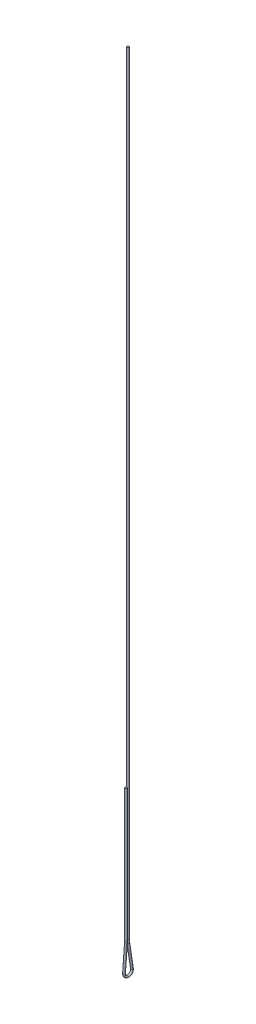
SolidWorks part; units mm, degrees
ref_plane "Front Plane" through (0, 0, 0) normal (0, 0, 1) x (1, 0, 0)
ref_plane "Top Plane" through (0, 0, 0) normal (0, 1, 0) x (1, 0, 0)
ref_plane "Right Plane" through (0, 0, 0) normal (1, 0, 0) x (0, 0, -1)
sketch "Sketch1" plane through (0, 0, 0) normal (1, 0, 0) x (0, 0, -1)
  line L1 (0, 21.5085) -> (0, 600)
  line L2 (0, 55) -> (0, -55) construction
  line L3 (55, 0) -> (-55, 0) construction
  line L4 (0.2263, 18.5085) -> (2.9661, 0.45)
  line L5 (-1.5, 20.7532) -> (-1.5, 120)
  line L6 (-1.5566, 19.2489) -> (-2.9915, 0.2256)
  circle A0 centre (0, 0) radius 2 construction
  arc A1 (-2.9915, 0.2256) -> (2.9661, 0.45) centre (0, 0) ccw
  arc A2 (0, 21.5085) -> (0.2263, 18.5085) centre (20, 21.5085) ccw
  arc A3 (-1.5, 20.7532) -> (-1.5566, 19.2489) centre (-21.5, 20.7532) cw
  point P15 (0, 20)
  point P18 (-1.5, 20)
  dimension "D1" = 4
  dimension "D2" = 6
  dimension "D8" = 20
  dimension "D3" = 20
  dimension "D4" = 580
  dimension "D5" = 1.5
  dimension "D6" = 100
  dimension "D7" = 20
ref_plane "Plane1" through (0, 120, 1.5) normal (0, 1, 0) x (-1, 0, 0)
sketch "Sketch2" plane through (0, 120, 1.5) normal (0, 1, 0) x (-1, 0, 0)
  circle A0 centre (0, 0) radius 0.75
  dimension "D1" = 1.5
sweep "Sweep1" add profiles "Sketch2" path "Sketch1"
